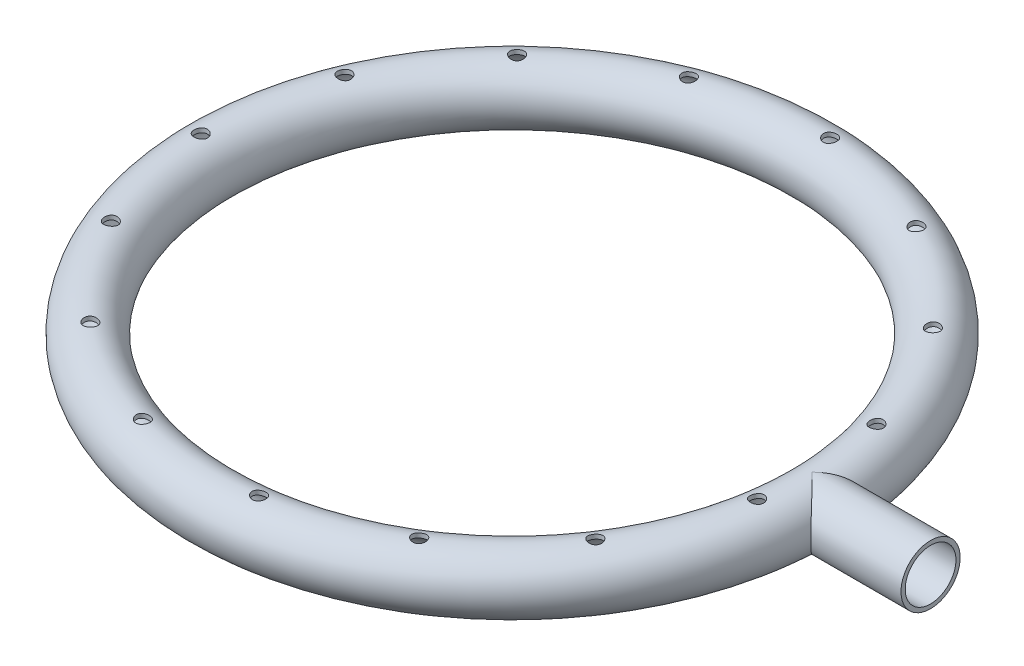
SolidWorks part; units mm, degrees
material "Wrought Copper"
ref_plane "Front Plane" through (0, 0, 0) normal (0, 0, 1) x (1, 0, 0)
ref_plane "Top Plane" through (0, 0, 0) normal (0, 1, 0) x (1, 0, 0)
ref_plane "Right Plane" through (0, 0, 0) normal (1, 0, 0) x (0, 0, -1)
sketch "Sketch1" plane through (0, 0, 0) normal (0, 0, 1) x (1, 0, 0)
  line L0 (-17.5, 0) -> (-177.5, 0)
  line L1 (-177.5, 0) -> (-177.5, 41.9844)
  circle A0 centre (0, 0) radius 15
  circle A1 centre (0, 0) radius 17.5
  dimension "D2" = 35
  dimension "D3" = 30
  dimension "D1" = 160
revolve "Revolve1" add sketch "Sketch1" angle 360 about L1
sketch "Sketch3" plane through (0, 0, 0) normal (1, 0, 0) x (0, 0, -1)
  circle A0 centre (0, 0) radius 17.5
  dimension "D1" = 35
extrude "Boss-Extrude1" add sketch "Sketch3" along normal blind 70
sketch "Sketch4" plane through (70, 0, 0) normal (1, 0, 0) x (0, 0, -1)
  circle A0 centre (0, 0) radius 15
  dimension "D1" = 30
extrude "Cut-Extrude1" cut sketch "Sketch4" against normal blind 70
sketch "Sketch5" plane through (0, 0, 0) normal (0, 0, 1) x (1, 0, 0)
  circle A0 centre (0, 0) radius 15
  dimension "D1" = 30
extrude "Cut-Extrude2" cut sketch "Sketch5" against normal blind 20 and the other way blind 30
sketch "Sketch6" plane through (0, 0, 0) normal (0, 1, 0) x (1, 0, 0)
  circle A16 centre (-2.8704, -29.7548) radius 4
  circle A18 centre (-30.0703, -98.2107) radius 4
  circle A19 centre (-82.7621, -149.685) radius 4
  circle A20 centre (-151.835, -175.2774) radius 4
  circle A21 centre (-225.3456, -170.5628) radius 4
  circle A22 centre (-290.5832, -136.3563) radius 4
  circle A23 centre (-336.2678, -78.5726) radius 4
  circle A24 centre (-354.4999, -7.2029) radius 4
  circle A25 centre (-342.1272, 65.4122) radius 4
  circle A26 centre (-301.2889, 126.7169) radius 4
  circle A27 centre (-239.0464, 166.1111) radius 4
  circle A28 centre (-166.1619, 176.7832) radius 4
  circle A29 centre (-95.238, 156.8879) radius 4
  circle A30 centre (-38.5378, 109.8652) radius 4
  circle A31 centre (-5.8655, 43.8459) radius 4
  point P0 (-177.5, 0)
  point P31 (-177.5, 0)
  dimension "D1" = 15
extrude "Cut-Extrude3" cut sketch "Sketch6" along normal through all
